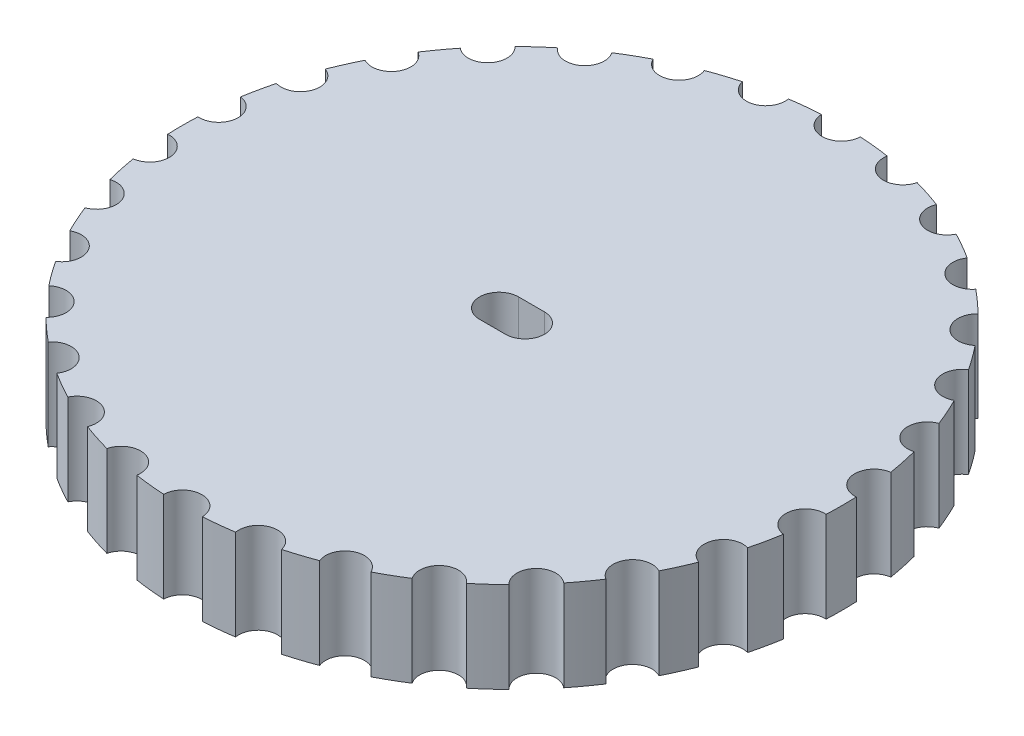
SolidWorks part; units mm, degrees
ref_plane "Front Plane" through (0, 0, 0) normal (0, 0, 1) x (1, 0, 0)
ref_plane "Top Plane" through (0, 0, 0) normal (0, 1, 0) x (1, 0, 0)
ref_plane "Right Plane" through (0, 0, 0) normal (1, 0, 0) x (0, 0, -1)
sketch "Sketch1" plane through (0, 0, 0) normal (0, 1, 0) x (1, 0, 0)
  circle A0 centre (0, 0) radius 25.4
  dimension "D1" = 50.8
extrude "Boss-Extrude1" add sketch "Sketch1" along normal blind 7 contours A0
sketch "Sketch3" plane through (0, 7, 0) normal (0, 1, 0) x (1, 0, 0)
  line L0 (-1, 0) -> (1, 0) construction
  line L3 (0, 25.4) -> (0, -25.4) construction
  line L4 (-1, 1.5) -> (1, 1.5)
  line L5 (-1, -1.5) -> (1, -1.5)
  circle A2 centre (0, 0) radius 25.4 construction
  arc A3 (-1, 1.5) -> (-1, -1.5) centre (-1, 0) ccw
  arc A4 (1, -1.5) -> (1, 1.5) centre (1, 0) ccw
  point P3 (0, 0)
  point P8 (-2.5, 0)
  point P9 (2.5, 0)
  point P16 (0, 1.5)
  point P17 (0, -1.5)
  dimension "D1" = 5
  dimension "D2" = 3
extrude "Cut-Extrude1" cut sketch "Sketch3" against normal blind 6
sketch "Sketch4" plane through (0, 7, 0) normal (0, 1, 0) x (1, 0, 0)
  line L0 (0, 25.4) -> (0, -25.4) construction
  line L1 (-25.4, 0) -> (25.4, 0) construction
  circle A5 centre (0, 25.4) radius 1.4966
  circle A6 centre (0, 0) radius 25.4 construction
  circle A7 centre (5.281, 24.8449) radius 1.4966
  circle A8 centre (10.3311, 23.2041) radius 1.4966
  circle A9 centre (14.9297, 20.549) radius 1.4966
  circle A10 centre (18.8759, 16.9959) radius 1.4966
  circle A11 centre (21.997, 12.7) radius 1.4966
  circle A12 centre (24.1568, 7.849) radius 1.4966
  circle A13 centre (25.2609, 2.655) radius 1.4966
  circle A14 centre (25.2609, -2.655) radius 1.4966
  circle A15 centre (24.1568, -7.849) radius 1.4966
  circle A16 centre (21.997, -12.7) radius 1.4966
  circle A17 centre (18.8759, -16.9959) radius 1.4966
  circle A18 centre (14.9297, -20.549) radius 1.4966
  circle A19 centre (10.3311, -23.2041) radius 1.4966
  circle A20 centre (5.281, -24.8449) radius 1.4966
  circle A21 centre (0, -25.4) radius 1.4966
  circle A22 centre (-5.281, -24.8449) radius 1.4966
  circle A23 centre (-10.3311, -23.2041) radius 1.4966
  circle A24 centre (-14.9297, -20.549) radius 1.4966
  circle A25 centre (-18.8759, -16.9959) radius 1.4966
  circle A26 centre (-21.997, -12.7) radius 1.4966
  circle A27 centre (-24.1568, -7.849) radius 1.4966
  circle A28 centre (-25.2609, -2.655) radius 1.4966
  circle A29 centre (-25.2609, 2.655) radius 1.4966
  circle A30 centre (-24.1568, 7.849) radius 1.4966
  circle A31 centre (-21.997, 12.7) radius 1.4966
  circle A32 centre (-18.8759, 16.9959) radius 1.4966
  circle A33 centre (-14.9297, 20.549) radius 1.4966
  circle A34 centre (-10.3311, 23.2041) radius 1.4966
  circle A35 centre (-5.281, 24.8449) radius 1.4966
  point P69 (0, 0)
  dimension "D1" = 30
extrude "Cut-Extrude2" cut sketch "Sketch4" against normal through all
